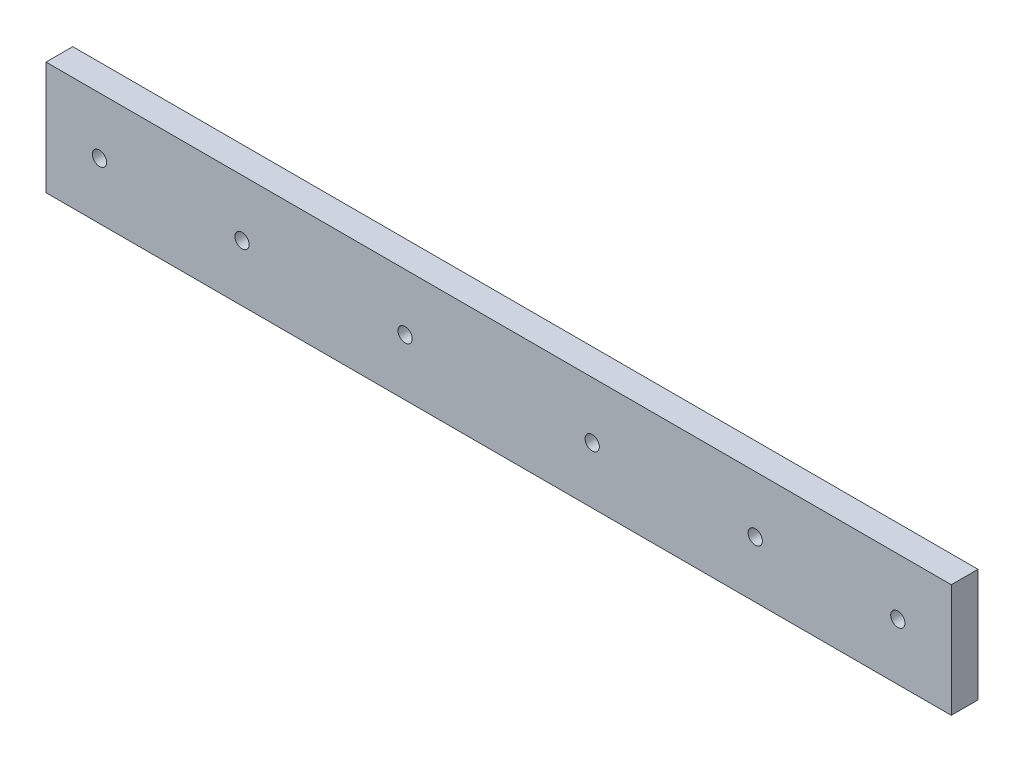
SolidWorks part; units mm, degrees
ref_plane "Plan de face" through (0, 0, 0) normal (0, 0, 1) x (1, 0, 0)
ref_plane "Plan de dessus" through (0, 0, 0) normal (0, 1, 0) x (1, 0, 0)
ref_plane "Plan de droite" through (0, 0, 0) normal (1, 0, 0) x (0, 0, -1)
sketch "Esquisse1" plane through (0, 0, 0) normal (0, 0, 1) x (1, 0, 0)
  line L1 (-101.6, -12.7) -> (101.6, -12.7)
  line L2 (-101.6, -12.7) -> (-101.6, 12.7)
  line L3 (-101.6, 12.7) -> (101.6, 12.7)
  line L4 (101.6, -12.7) -> (101.6, 12.7)
  line L5 (-101.6, -12.7) -> (101.6, 12.7) construction
  line L6 (-101.6, 12.7) -> (101.6, -12.7) construction
  point P0 (0, 0)
  dimension "D1" = 203.2
  dimension "D2" = 25.4
extrude "Boss.-Extru.1" add sketch "Esquisse1" along normal blind 6
sketch "Esquisse2" plane through (0, 0, 6) normal (0, 0, 1) x (1, 0, 0)
  line L0 (-89.6, 0) -> (89.6, 0) construction
  line L2 (-101.6, 12.7) -> (-101.6, -12.7) construction
  line L3 (101.6, 12.7) -> (-101.6, 12.7) construction
  line L4 (101.6, -12.7) -> (101.6, 12.7) construction
  point P0 (-21, 0)
  point P1 (21, 0)
  point P2 (89.6, 0)
  point P3 (-89.6, 0)
  point P6 (-57.6, 0)
  point P10 (-101.6, 0)
  point P11 (0, 0)
  point P14 (0, 12.7)
  point P16 (57.6, 0)
  point P17 (0, 0)
  point P18 (0, 0)
  point P19 (0, 0)
  dimension "D1" = 42
  dimension "D2" = 21
  dimension "D3" = 32
  dimension "D4" = 12
  dimension "D5" = 32
hole_wizard "Dégagement M31" positions "Esquisse3D1" profile "Esquisse3" hole size "M3" standard "Ansi Metric" end condition through all
sketch3d "Esquisse3D1"
  point P0 (89.6, 0, 6)
  point P2 (57.6, 0, 6)
  point P4 (21, 0, 6)
  point P6 (-21, 0, 6)
  point P8 (-57.6, 0, 6)
  point P10 (-89.6, 0, 6)
  point P13 (-96.5936, 3.6653, 0)
  point P15 (0, 0, 0)
  point P17 (0, 0, 0)
  point P19 (0, 0, 0)
  point P20 (0, 0, 0)
  point P22 (0, 0, 0)
  point P24 (0, 0, 0)
  point P26 (85.6357, 3.7904, 0)
sketch "Esquisse3" plane through (89.6, 0, 6) normal (1, 0, 0) x (0, -1, 0)
  line L0 (0, 0) -> (0, 6)
  line L1 (0, 6) -> (1.6, 6)
  line L2 (1.6, 6) -> (1.6, 0)
  line L5 (1.6, 0) -> (0, 0)
  line L11 (0, -6.35) -> (0, 107.95) construction
  dimension "Diamètre du perçage jusqu'au prochain" = 3.2
  dimension "Profondeur du perçage jusqu'au prochain" = 6
